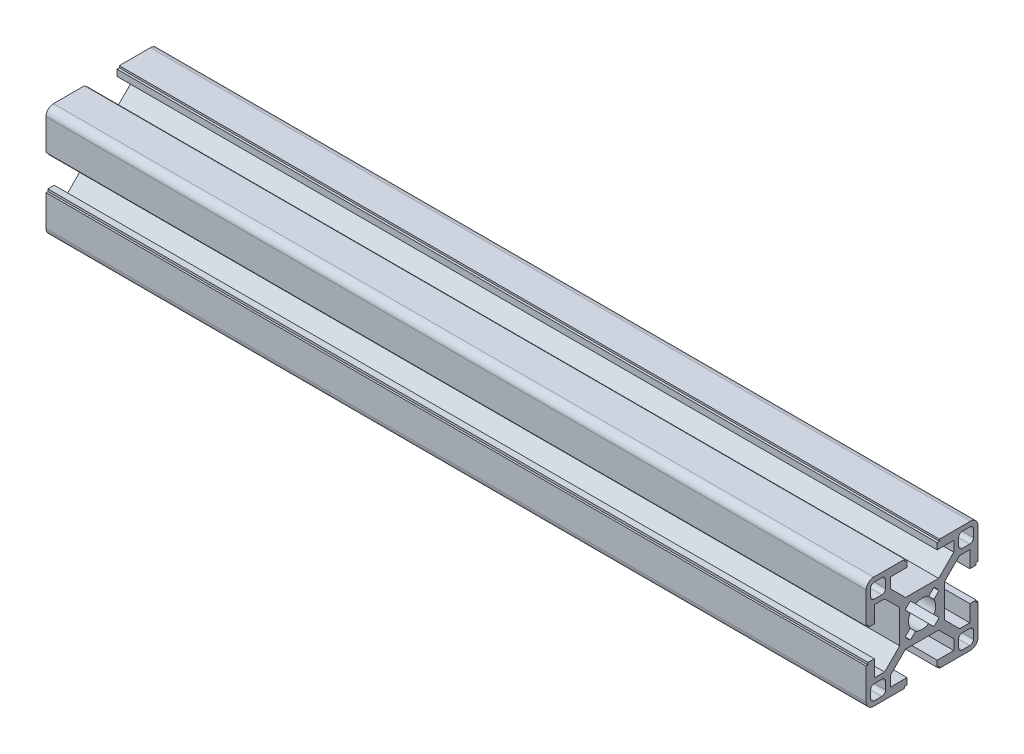
SolidWorks part; units mm, degrees
ref_plane "Ebene vorne" through (0, 0, 0) normal (0, 0, 1) x (1, 0, 0)
ref_plane "Ebene oben" through (0, 0, 0) normal (0, 1, 0) x (1, 0, 0)
ref_plane "Ebene rechts" through (0, 0, 0) normal (1, 0, 0) x (0, 0, -1)
sketch "Skizze1" plane through (0, 0, 0) normal (1, 0, 0) x (0, 0, -1)
  line L0 (8.5, 10.0556) -> (4.4444, 6)
  line L1 (13, 15) -> (-13, 15)
  line L2 (15, 13) -> (15, -13)
  line L3 (13, -15) -> (-13, -15)
  line L4 (-15, 13) -> (-15, -13)
  line L5 (15, 15) -> (-15, -15) construction
  line L6 (15, -15) -> (-15, 15) construction
  line L7 (6, 6) -> (-6, 6)
  line L8 (6, 6) -> (6, -6)
  line L9 (6, -6) -> (-6, -6)
  line L10 (-6, 6) -> (-6, -6)
  line L11 (6, 6) -> (-6, -6) construction
  line L12 (6, -6) -> (-6, 6) construction
  line L13 (8.5, 12.8) -> (-8.5, 12.8)
  line L14 (8.5, 12.8) -> (8.5, 6)
  line L15 (8.5, 6) -> (-8.5, 6)
  line L16 (-8.5, 12.8) -> (-8.5, 6)
  line L17 (4.05, 15) -> (-4.05, 15)
  line L18 (4.05, 15) -> (4.05, 12.8)
  line L19 (4.05, 12.8) -> (-4.05, 12.8)
  line L20 (-4.05, 15) -> (-4.05, 12.8)
  line L21 (-8.5, 10.0556) -> (-4.4444, 6)
  line L22 (3.1172, 4.5314) -> (1.7751, 3.1893)
  line L23 (-3.1172, 4.5314) -> (-1.7751, 3.1893)
  line L24 (15, -4.05) -> (12.8, -4.05)
  line L25 (4.05, 15) -> (4.6516, 15)
  line L26 (4.05, 15) -> (4.05, 14.5)
  line L27 (4.05, 14.5) -> (4.6516, 14.5)
  line L28 (4.6516, 15) -> (4.6516, 14.5)
  line L29 (-4.05, 15) -> (-4.6516, 15)
  line L30 (-4.05, 15) -> (-4.05, 14.5)
  line L31 (-4.05, 14.5) -> (-4.6516, 14.5)
  line L32 (-4.6516, 15) -> (-4.6516, 14.5)
  line L33 (15, -4.6516) -> (14.5, -4.6516)
  line L34 (14.5, -4.05) -> (14.5, -4.6516)
  line L35 (14.5, 4.05) -> (14.5, 4.6516)
  line L36 (15, 4.6516) -> (14.5, 4.6516)
  line L37 (15, 4.05) -> (12.8, 4.05)
  line L38 (12.8, 8.5) -> (6, 8.5)
  line L39 (12.8, -8.5) -> (12.8, 8.5)
  line L40 (12.8, -8.5) -> (6, -8.5)
  line L41 (10.0556, -8.5) -> (6, -4.4444)
  line L42 (10.0556, 8.5) -> (6, 4.4444)
  line L43 (4.5314, -3.1172) -> (3.1893, -1.7751)
  line L44 (4.5314, 3.1172) -> (3.1893, 1.7751)
  line L45 (-4.05, -15) -> (-4.05, -12.8)
  line L46 (-4.6516, -15) -> (-4.6516, -14.5)
  line L47 (-4.05, -14.5) -> (-4.6516, -14.5)
  line L48 (4.05, -14.5) -> (4.6516, -14.5)
  line L49 (4.6516, -15) -> (4.6516, -14.5)
  line L50 (4.05, -15) -> (4.05, -12.8)
  line L51 (8.5, -12.8) -> (8.5, -6)
  line L52 (-8.5, -12.8) -> (8.5, -12.8)
  line L53 (-8.5, -12.8) -> (-8.5, -6)
  line L54 (-8.5, -10.0556) -> (-4.4444, -6)
  line L55 (8.5, -10.0556) -> (4.4444, -6)
  line L56 (-3.1172, -4.5314) -> (-1.7751, -3.1893)
  line L57 (3.1172, -4.5314) -> (1.7751, -3.1893)
  line L58 (-15, 4.05) -> (-12.8, 4.05)
  line L59 (-15, 4.6516) -> (-14.5, 4.6516)
  line L60 (-14.5, 4.05) -> (-14.5, 4.6516)
  line L61 (-14.5, -4.05) -> (-14.5, -4.6516)
  line L62 (-15, -4.6516) -> (-14.5, -4.6516)
  line L63 (-15, -4.05) -> (-12.8, -4.05)
  line L64 (-12.8, -8.5) -> (-6, -8.5)
  line L65 (-12.8, 8.5) -> (-12.8, -8.5)
  line L66 (-12.8, 8.5) -> (-6, 8.5)
  line L67 (-10.0556, 8.5) -> (-6, 4.4444)
  line L68 (-10.0556, -8.5) -> (-6, -4.4444)
  line L69 (-4.5314, 3.1172) -> (-3.1893, 1.7751)
  line L70 (-4.5314, -3.1172) -> (-3.1893, -1.7751)
  line L71 (6, -8.5) -> (6, 8.5)
  line L72 (-8.5, -6) -> (8.5, -6)
  line L73 (-6, 8.5) -> (-6, -8.5)
  line L75 (12.8, 13.8) -> (10.8, 13.8)
  line L76 (13.8, 12.8) -> (13.8, 10.8)
  line L77 (12.8, 9.8) -> (10.8, 9.8)
  line L78 (9.8, 12.8) -> (9.8, 10.8)
  line L79 (13.8, 13.8) -> (9.8, 9.8) construction
  line L80 (13.8, 9.8) -> (9.8, 13.8) construction
  line L81 (-10.8, 13.8) -> (-12.8, 13.8)
  line L82 (-9.8, 12.8) -> (-9.8, 10.8)
  line L83 (-10.8, 9.8) -> (-12.8, 9.8)
  line L84 (-13.8, 12.8) -> (-13.8, 10.8)
  line L85 (-9.8, 13.8) -> (-13.8, 9.8) construction
  line L86 (-9.8, 9.8) -> (-13.8, 13.8) construction
  line L87 (12.8, -9.8) -> (10.8, -9.8)
  line L88 (13.8, -10.8) -> (13.8, -12.8)
  line L89 (12.8, -13.8) -> (10.8, -13.8)
  line L90 (9.8, -10.8) -> (9.8, -12.8)
  line L91 (13.8, -9.8) -> (9.8, -13.8) construction
  line L92 (13.8, -13.8) -> (9.8, -9.8) construction
  line L93 (-10.8, -9.8) -> (-12.8, -9.8)
  line L94 (-9.8, -10.8) -> (-9.8, -12.8)
  line L95 (-10.8, -13.8) -> (-12.8, -13.8)
  line L96 (-13.8, -10.8) -> (-13.8, -12.8)
  line L97 (-9.8, -9.8) -> (-13.8, -13.8) construction
  line L98 (-9.8, -13.8) -> (-13.8, -9.8) construction
  arc A0 (13, -15) -> (15, -13) centre (13, -13) ccw
  arc A1 (-13, -15) -> (-15, -13) centre (-13, -13) cw
  arc A2 (-15, 13) -> (-13, 15) centre (-13, 13) cw
  arc A3 (13, 15) -> (15, 13) centre (13, 13) cw
  circle A4 centre (0, 0) radius 3.65
  circle A5 centre (0, 0) radius 5.5
  circle A6 centre (0, 0) radius 3.65
  circle A7 centre (0, 0) radius 3.65
  circle A8 centre (0, 0) radius 3.65
  arc A9 (12.8, -13.8) -> (13.8, -12.8) centre (12.8, -12.8) ccw
  arc A10 (13.8, -10.8) -> (12.8, -9.8) centre (12.8, -10.8) ccw
  arc A11 (9.8, -12.8) -> (10.8, -13.8) centre (10.8, -12.8) ccw
  arc A12 (9.8, -10.8) -> (10.8, -9.8) centre (10.8, -10.8) cw
  arc A13 (-10.8, -13.8) -> (-9.8, -12.8) centre (-10.8, -12.8) ccw
  arc A14 (-10.8, -9.8) -> (-9.8, -10.8) centre (-10.8, -10.8) cw
  arc A15 (-13.8, -12.8) -> (-12.8, -13.8) centre (-12.8, -12.8) ccw
  arc A16 (-13.8, -10.8) -> (-12.8, -9.8) centre (-12.8, -10.8) cw
  arc A17 (-12.8, 9.8) -> (-13.8, 10.8) centre (-12.8, 10.8) cw
  arc A18 (-10.8, 9.8) -> (-9.8, 10.8) centre (-10.8, 10.8) ccw
  arc A19 (-13.8, 12.8) -> (-12.8, 13.8) centre (-12.8, 12.8) cw
  arc A20 (-10.8, 13.8) -> (-9.8, 12.8) centre (-10.8, 12.8) cw
  arc A21 (13.8, 10.8) -> (12.8, 9.8) centre (12.8, 10.8) cw
  arc A22 (10.8, 9.8) -> (9.8, 10.8) centre (10.8, 10.8) cw
  arc A23 (10.8, 13.8) -> (9.8, 12.8) centre (10.8, 12.8) ccw
  arc A24 (12.8, 13.8) -> (13.8, 12.8) centre (12.8, 12.8) cw
  point P0 (0, 0)
  point P33 (0, 12.8)
  point P34 (0, 15)
  point P36 (0, 12.8)
  point P50 (11.8, 11.8)
  point P122 (0, 0)
  point P125 (-11.8, 11.8)
  point P129 (0, 0)
  point P131 (11.8, -11.8)
  point P136 (-11.8, -11.8)
  dimension "D2" = 2
  dimension "D3" = 7.3
  dimension "D4" = 11
  dimension "D20" = 1
  dimension "D1" = 30
  dimension "D5" = 12
  dimension "D6" = 17
  dimension "D7" = 8.1
  dimension "D8" = 2.2
  dimension "D9" = 9
  dimension "D10" = 1.1
  dimension "D11" = 1.1
  dimension "D12" = 1
  dimension "D13" = 1
  dimension "D14" = 0.5
  dimension "D15" = 0.6016
  dimension "D18" = 4
  dimension "D19" = 1.2
  dimension "D16" = 4
  dimension "D17" = 4
extrude "Aufsatz-Linear austragen1" add sketch "Skizze1" along normal blind 220 contours A3 L1 L28 L27 L18 L13 L14 L38 L39 L37 L35 L36 L2 | L42 L38 L14 | L71 L15 L42 L14 L38 L0 | L42 L15 L8 | L7 L71 L0 | L38 L14 L0 | L7 L15 L10 L9 L8 A5 | L43 A5 L44 A4 | L22 A5 L23 A4 | L69 A5 L70 A4 | L56 A5 L57 A4 | L3 A0 L2 L33 L34 L24 L39 L40 L51 L52 L50 L48 L49 | L51 L40 L41 | L72 L71 L55 L40 L51 L41 | L8 L72 L41 | L55 L71 L9 | L55 L51 L40 | L73 L72 L68 L53 L64 L54 | L68 L72 L10 | L9 L73 L54 | L68 L64 L53 | L64 L53 L54 | A1 L3 L46 L47 L45 L52 L53 L64 L65 L63 L61 L62 L4 | A2 L4 L59 L60 L58 L65 L66 L16 L13 L20 L31 L32 L1 | L66 L67 L16 | L16 L66 L21 | L73 L21 L66 L16 L67 L15 | L21 L73 L15 | L15 L67 L10
